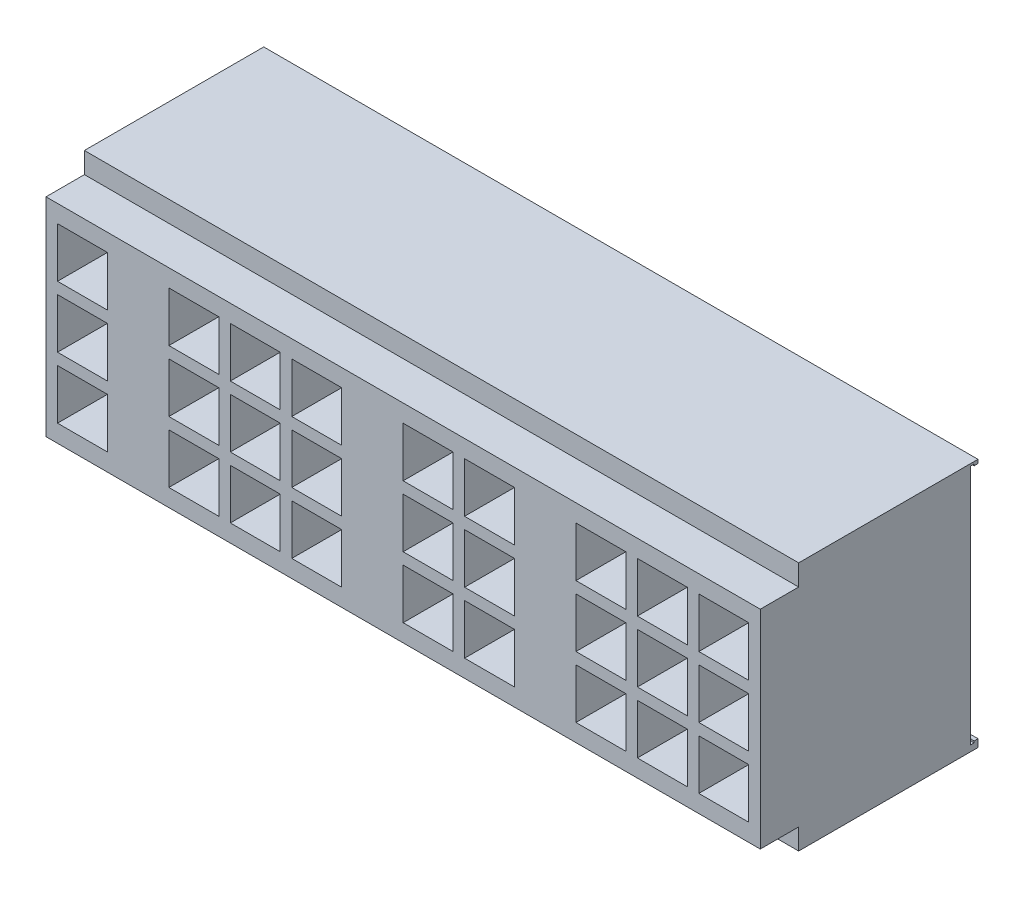
SolidWorks part; units mm, degrees
ref_plane "Plan de face" through (0, 0, 0) normal (0, 0, 1) x (1, 0, 0)
ref_plane "Plan de dessus" through (0, 0, 0) normal (0, 1, 0) x (1, 0, 0)
ref_plane "Plan de droite" through (0, 0, 0) normal (1, 0, 0) x (0, 0, -1)
sketch "Esquisse1" plane through (0, 0, 0) normal (0, 0, 1) x (1, 0, 0)
  line L1 (-93, -51) -> (93, -51)
  line L2 (-93, -51) -> (-93, 0)
  line L3 (-93, 0) -> (93, 0)
  line L4 (93, -51) -> (93, 0)
  line L13 (0, 49979.1071) -> (0, -49979.1071) construction
  point P0 (0, 0)
  point P16 (0, -51)
  point P17 (0, 0)
  point P27 (0, 0)
  dimension "D1" = 186
  dimension "D2" = 51
extrude "Boss.-Extru.1" add sketch "Esquisse1" along normal blind 20
sketch "Esquisse7" plane through (0, 0, 20) normal (0, 0, 1) x (1, 0, 0)
  line L0 (93, 0) -> (-93, 0) construction
  line L1 (-90, -3) -> (-77, -3)
  line L2 (-90, -3) -> (-90, -16)
  line L3 (-90, -16) -> (-77, -16)
  line L4 (-77, -3) -> (-77, -16)
  line L5 (-90, -3) -> (-77, -16) construction
  line L6 (-90, -16) -> (-77, -3) construction
  line L7 (-93, 0) -> (-93, -51) construction
  point P0 (-83.5, -9.5)
  dimension "D1" = 13
  dimension "D2" = 13
  dimension "D3" = 3
  dimension "D4" = 3
extrude "Enlèv. mat.-Extru.5" cut sketch "Esquisse7" against normal blind 91
pattern_linear "Répétition linéaire5" count 3 spacing 16 along (0, -1, 0) of "Enlèv. mat.-Extru.5"
sketch "Esquisse8" plane through (0, 0, 20) normal (0, 0, 1) x (1, 0, 0)
  line L0 (93, 0) -> (-93, 0) construction
  line L1 (-61, -3) -> (-48, -3)
  line L2 (-61, -3) -> (-61, -16)
  line L3 (-61, -16) -> (-48, -16)
  line L4 (-48, -3) -> (-48, -16)
  line L5 (-61, -3) -> (-48, -16) construction
  line L6 (-61, -16) -> (-48, -3) construction
  line L7 (-77, -16) -> (-77, -3) construction
  point P0 (-54.5, -9.5)
  dimension "D1" = 13
  dimension "D2" = 13
  dimension "D3" = 3
  dimension "D4" = 16
extrude "Enlèv. mat.-Extru.6" cut sketch "Esquisse8" against normal blind 103
pattern_linear "Répétition linéaire6" count 3 spacing 16 along (0, -1, 0) count 3 spacing 16 along (1, 0, 0) of "Enlèv. mat.-Extru.6"
sketch "Esquisse9" plane through (0, 0, 20) normal (0, 0, 1) x (1, 0, 0)
  line L0 (-16, -16) -> (-16, -3) construction
  line L1 (0, -3) -> (13, -3)
  line L2 (0, -3) -> (0, -16)
  line L3 (0, -16) -> (13, -16)
  line L4 (13, -3) -> (13, -16)
  line L5 (0, -3) -> (13, -16) construction
  line L6 (0, -16) -> (13, -3) construction
  line L7 (93, 0) -> (-93, 0) construction
  point P0 (6.5, -9.5)
  dimension "D1" = 13
  dimension "D2" = 13
  dimension "D3" = 16
  dimension "D4" = 3
extrude "Enlèv. mat.-Extru.7" cut sketch "Esquisse9" against normal blind 77
pattern_linear "Répétition linéaire7" count 3 spacing 16 along (0, -1, 0) count 2 spacing 16 along (1, 0, 0) of "Enlèv. mat.-Extru.7"
sketch "Esquisse10" plane through (0, 0, 20) normal (0, 0, 1) x (1, 0, 0)
  line L0 (29, -16) -> (29, -3) construction
  line L1 (45, -3) -> (58, -3)
  line L2 (45, -3) -> (45, -16)
  line L3 (45, -16) -> (58, -16)
  line L4 (58, -3) -> (58, -16)
  line L5 (45, -3) -> (58, -16) construction
  line L6 (45, -16) -> (58, -3) construction
  line L7 (93, 0) -> (-93, 0) construction
  point P0 (51.5, -9.5)
  dimension "D1" = 13
  dimension "D2" = 13
  dimension "D3" = 16
  dimension "D4" = 3
extrude "Enlèv. mat.-Extru.8" cut sketch "Esquisse10" against normal blind 78
pattern_linear "Répétition linéaire8" count 3 spacing 16 along (1, 0, 0) count 3 spacing 16 along (0, -1, 0) of "Enlèv. mat.-Extru.8"
sketch "Esquisse14" plane through (0, -51, 0) normal (0, -1, 0) x (1, 0, 0)
  line L0 (0, 0) -> (-15.3262, 0) construction
  line L1 (-12.6631, 0) -> (-2.6631, 0)
  line L2 (-12.6631, 0) -> (-12.6631, 5)
  line L3 (-12.6631, 5) -> (-2.6631, 5)
  line L4 (-2.6631, 0) -> (-2.6631, 5)
  line L5 (-12.6631, 0) -> (-2.6631, 5) construction
  line L6 (-12.6631, 5) -> (-2.6631, 0) construction
  line L7 (-93, 0) -> (93, 0) construction
  point P0 (-7.6631, 2.5)
  point P5 (-15.3262, 0)
  point P6 (0, 0)
  point P10 (0, 0)
  point P12 (-7.6631, 0)
  point P13 (-7.6631, 0)
  dimension "D1" = 10
  dimension "D2" = 5
extrude "Boss.-Extru.3" add sketch "Esquisse14" along normal blind 7
sketch "Esquisse25" plane through (0, 0, 0) normal (0, 1, 0) x (1, 0, 0)
  line L1 (-93, 0) -> (93, 0)
  line L2 (-93, 0) -> (-93, -20)
  line L3 (-93, -20) -> (93, -20)
  line L4 (93, 0) -> (93, -20)
extrude "Boss.-Extru.7" add sketch "Esquisse25" along normal blind 7
sketch "Esquisse18" plane through (0, -51, 0) normal (0, -1, 0) x (1, 0, 0)
  line L0 (-93, 0) -> (93, 0)
  line L2 (93, 0) -> (93, 20)
  line L3 (93, 20) -> (-93, 20)
  line L4 (-93, 20) -> (-93, 0)
extrude "Boss.-Extru.5" add sketch "Esquisse18" along normal blind 7
sketch "Esquisse16" plane through (-93, 0, 0) normal (-1, 0, 0) x (0, 0, 1)
  line L0 (20, -58) -> (0, -58) construction
  line L1 (20, 7) -> (20, -58) construction
  line L3 (20, -53) -> (16.7, -53)
  line L4 (16.7, -53) -> (16.7, 2)
  line L5 (16.7, 2) -> (20, 2)
  line L6 (20, 2) -> (20, -53)
  line L8 (0, 7) -> (20, 7) construction
  point P1 (18.35, -53)
  dimension "D1" = 5
  dimension "D4" = 5
  dimension "D5" = 3.3
extrude "Enlèv. mat.-Extru.11" cut sketch "Esquisse16" against normal blind 184
sketch "Esquisse15" plane through (0, 0, 0) normal (0, 0, -1) x (-1, 0, 0)
  circle A0 centre (8.4823, -42.4466) radius 1
  circle A1 centre (8.4823, -9.749) radius 1
  circle A2 centre (68.823, -42.4466) radius 1
  circle A3 centre (68.823, -9.749) radius 1
  circle A4 centre (-37.1355, -42.4466) radius 1
  circle A5 centre (-39.2159, -11.2606) radius 1
  dimension "D1" = 2
  dimension "D2" = 2
  dimension "D3" = 2
  dimension "D4" = 2
  dimension "D5" = 2
  dimension "D6" = 2
extrude "Enlèv. mat.-Extru.10" cut sketch "Esquisse15" against normal blind 7
sketch "Esquisse24" plane through (0, 0, 0) normal (0, 0, -1) x (-1, 0, 0)
  line L0 (77, -48) -> (90, -48) construction
  line L1 (88.5, -48) -> (78.5, -48)
  line L2 (88.5, -48) -> (88.5, -50)
  line L3 (88.5, -50) -> (78.5, -50)
  line L4 (78.5, -48) -> (78.5, -50)
  line L5 (48, -48) -> (61, -48) construction
  line L6 (59.5, -48) -> (49.5, -48)
  line L7 (59.5, -48) -> (59.5, -50)
  line L8 (59.5, -50) -> (49.5, -50)
  line L9 (49.5, -48) -> (49.5, -50)
  line L10 (32, -48) -> (45, -48) construction
  line L11 (43.5, -48) -> (33.5, -48)
  line L12 (43.5, -48) -> (43.5, -50)
  line L13 (43.5, -50) -> (33.5, -50)
  line L14 (33.5, -48) -> (33.5, -50)
  line L15 (16, -48) -> (29, -48) construction
  line L16 (27.5, -48) -> (17.5, -48)
  line L17 (27.5, -48) -> (27.5, -50)
  line L18 (27.5, -50) -> (17.5, -50)
  line L19 (17.5, -48) -> (17.5, -50)
  line L20 (-13, -48) -> (0, -48) construction
  line L21 (-1.5, -48) -> (-11.5, -48)
  line L22 (-1.5, -48) -> (-1.5, -50)
  line L23 (-1.5, -50) -> (-11.5, -50)
  line L24 (-11.5, -48) -> (-11.5, -50)
  line L25 (-29, -48) -> (-16, -48) construction
  line L26 (-17.5, -48) -> (-27.5, -48)
  line L27 (-17.5, -48) -> (-17.5, -50)
  line L28 (-17.5, -50) -> (-27.5, -50)
  line L29 (-27.5, -48) -> (-27.5, -50)
  line L30 (-58, -48) -> (-45, -48) construction
  line L31 (-46.5, -48) -> (-56.5, -48)
  line L32 (-46.5, -48) -> (-46.5, -50)
  line L33 (-46.5, -50) -> (-56.5, -50)
  line L34 (-56.5, -48) -> (-56.5, -50)
  line L35 (-74, -48) -> (-61, -48) construction
  line L36 (-62.5, -48) -> (-72.5, -48)
  line L37 (-62.5, -48) -> (-62.5, -50)
  line L38 (-62.5, -50) -> (-72.5, -50)
  line L39 (-72.5, -48) -> (-72.5, -50)
  line L40 (-90, -48) -> (-77, -48) construction
  line L41 (-78.5, -48) -> (-88.5, -48)
  line L42 (-78.5, -48) -> (-78.5, -50)
  line L43 (-78.5, -50) -> (-88.5, -50)
  line L44 (-88.5, -48) -> (-88.5, -50)
  line L45 (-77, -3) -> (-90, -3) construction
  line L46 (-78.5, -3) -> (-88.5, -3)
  line L47 (-78.5, -3) -> (-78.5, -1)
  line L48 (-78.5, -1) -> (-88.5, -1)
  line L49 (-88.5, -3) -> (-88.5, -1)
  line L50 (-61, -3) -> (-74, -3) construction
  line L51 (-62.5, -3) -> (-72.5, -3)
  line L52 (-62.5, -3) -> (-62.5, -1)
  line L53 (-62.5, -1) -> (-72.5, -1)
  line L54 (-72.5, -3) -> (-72.5, -1)
  line L55 (-45, -3) -> (-58, -3) construction
  line L56 (-46.5, -3) -> (-56.5, -3)
  line L57 (-46.5, -3) -> (-46.5, -1)
  line L58 (-46.5, -1) -> (-56.5, -1)
  line L59 (-56.5, -3) -> (-56.5, -1)
  line L60 (-16, -3) -> (-29, -3) construction
  line L61 (-17.5, -3) -> (-27.5, -3)
  line L62 (-17.5, -3) -> (-17.5, -1)
  line L63 (-17.5, -1) -> (-27.5, -1)
  line L64 (-27.5, -3) -> (-27.5, -1)
  line L65 (0, -3) -> (-13, -3) construction
  line L66 (-1.5, -3) -> (-11.5, -3)
  line L67 (-1.5, -3) -> (-1.5, -1)
  line L68 (-1.5, -1) -> (-11.5, -1)
  line L69 (-11.5, -3) -> (-11.5, -1)
  line L70 (29, -3) -> (16, -3) construction
  line L71 (17.5, -3) -> (27.5, -3)
  line L72 (17.5, -3) -> (17.5, -1)
  line L73 (17.5, -1) -> (27.5, -1)
  line L74 (27.5, -3) -> (27.5, -1)
  line L75 (45, -3) -> (32, -3) construction
  line L76 (33.5, -3) -> (43.5, -3)
  line L77 (33.5, -3) -> (33.5, -1)
  line L78 (33.5, -1) -> (43.5, -1)
  line L79 (43.5, -3) -> (43.5, -1)
  line L80 (61, -3) -> (48, -3) construction
  line L81 (49.5, -3) -> (59.5, -3)
  line L82 (49.5, -3) -> (49.5, -1)
  line L83 (49.5, -1) -> (59.5, -1)
  line L84 (59.5, -3) -> (59.5, -1)
  line L85 (90, -3) -> (77, -3) construction
  line L86 (78.5, -3) -> (88.5, -3)
  line L87 (78.5, -3) -> (78.5, -1)
  line L88 (78.5, -1) -> (88.5, -1)
  line L89 (88.5, -3) -> (88.5, -1)
  point P108 (83.5, -48)
  point P109 (54.5, -48)
  point P110 (38.5, -48)
  point P111 (22.5, -48)
  point P112 (-6.5, -48)
  point P113 (-22.5, -48)
  point P114 (-51.5, -48)
  point P115 (-67.5, -48)
  point P116 (-83.5, -48)
  point P117 (-83.5, -3)
  point P118 (-67.5, -3)
  point P119 (-51.5, -3)
  point P120 (-22.5, -3)
  point P121 (-6.5, -3)
  point P122 (22.5, -3)
  point P123 (38.5, -3)
  point P124 (54.5, -3)
  point P125 (83.5, -3)
  point P126 (83.5, -3)
  point P128 (54.5, -3)
  point P130 (38.5, -3)
  point P132 (22.5, -3)
  point P134 (-6.5, -3)
  point P136 (-22.5, -3)
  point P138 (-51.5, -3)
  point P140 (-67.5, -3)
  point P143 (-83.5, -3)
  point P145 (-83.5, -48)
  point P148 (-51.5, -48)
  point P150 (-22.5, -48)
  point P152 (-6.5, -48)
  point P154 (22.5, -48)
  point P156 (38.5, -48)
  point P159 (54.5, -48)
  point P161 (83.5, -48)
  dimension "D1" = 10
  dimension "D2" = 10
  dimension "D3" = 10
  dimension "D4" = 10
  dimension "D5" = 10
  dimension "D6" = 10
  dimension "D7" = 10
  dimension "D8" = 10
  dimension "D9" = 10
  dimension "D10" = 10
  dimension "D11" = 10
  dimension "D12" = 10
  dimension "D13" = 10
  dimension "D14" = 10
  dimension "D15" = 10
  dimension "D16" = 10
  dimension "D17" = 10
  dimension "D18" = 10
  dimension "D19" = 2
  dimension "D20" = 2
  dimension "D21" = 2
  dimension "D22" = 2
  dimension "D23" = 2
  dimension "D24" = 2
  dimension "D25" = 2
  dimension "D26" = 2
  dimension "D27" = 2
  dimension "D28" = 2
  dimension "D29" = 2
  dimension "D30" = 2
  dimension "D31" = 2
  dimension "D32" = 2
  dimension "D33" = 2
  dimension "D34" = 2
  dimension "D35" = 2
  dimension "D36" = 2
extrude "Enlèv. mat.-Extru.12" cut sketch "Esquisse24" against normal blind 1
sketch "Esquisse19" plane through (0, 0, 0) normal (0, 0, -1) x (-1, 0, 0)
  line L0 (-93, -58) -> (-93, 7) construction
  line L1 (93, -58) -> (-93, -58)
  line L2 (93, -58) -> (93, -56)
  line L3 (93, -56) -> (-93, -56)
  line L4 (-93, -58) -> (-93, -56)
  line L5 (93, 7) -> (93, -58) construction
  line L6 (-93, 7) -> (93, 7)
  line L7 (-93, 7) -> (-93, 5)
  line L8 (-93, 5) -> (93, 5)
  line L9 (93, 7) -> (93, 5)
  line L11 (-93, -56) -> (-91, -56)
  line L12 (-93, -56) -> (-93, 5)
  line L13 (-93, 5) -> (-91, 5)
  line L14 (-91, -56) -> (-91, 5)
  line L15 (93, 5) -> (91, 5)
  line L16 (93, 5) -> (93, -56)
  line L17 (93, -56) -> (91, -56)
  line L18 (91, 5) -> (91, -56)
  dimension "D1" = 2
  dimension "D2" = 2
  dimension "D3" = 2
  dimension "D4" = 2
extrude "Boss.-Extru.8" add sketch "Esquisse19" along normal blind 40 contours L4 L1 L2 L3 | L8 L18 L3 L16 | L9 L6 L7 L8 | L3 L14 L8 L12
sketch "Esquisse26" plane through (-93, 0, 0) normal (-1, 0, 0) x (0, 0, 1)
  line L0 (-40, -58) -> (-10, 7) construction
  line L1 (-40, 7) -> (20, 7) construction
  line L2 (-40, 7) -> (-10, -58) construction
  line L3 (20, -58) -> (-40, -58) construction
  circle A0 centre (-25, -25.5) radius 1.75
  dimension "D1" = 3.5
extrude "Enlèv. mat.-Extru.14" cut sketch "Esquisse26" against normal blind 30
sketch "Esquisse27" plane through (-93, 0, 0) normal (-1, 0, 0) x (0, 0, 1)
  line L1 (6.7, 2) -> (6.7, 7)
  line L2 (-40, 7) -> (20, 7) construction
  line L3 (6.7, 7) -> (20, 7)
  line L4 (20, 7) -> (20, -58)
  line L5 (20, -58) -> (6.7, -58)
  line L6 (20, -58) -> (-40, -58) construction
  line L7 (16.7, 1.55) -> (6.7, 1.55)
  line L8 (6.7, -53) -> (6.7, -58)
  line L9 (16.7, -53) -> (16.7, 2)
  line L10 (6.7, -53) -> (6.7, -52.55)
  line L11 (6.7, -52.55) -> (16.7, -52.55)
  line L12 (6.7, 1.55) -> (6.7, 2)
  point P16 (16.7, -52.55)
  point P17 (16.7, 1.55)
  dimension "D1" = 10
  dimension "D2" = 10
  dimension "D3" = 0.45
  dimension "D4" = 0.45
extrude "Enlèv. mat.-Extru.16" cut sketch "Esquisse27" against normal through all
sketch "Esquisse29" plane through (0, 0, -40) normal (0, 0, -1) x (-1, 0, 0)
  line L0 (-91, -56) -> (-93, -56) construction
  line L1 (-93, -58) -> (-93, 7) construction
sketch "Esquisse30" plane through (93, 0, 0) normal (1, 0, 0) x (0, 0, -1)
  line L1 (38, -56) -> (38, -56.45)
  line L2 (38, -56.45) -> (39, -56.45)
  line L3 (40, -58) -> (40, 7) construction
  line L4 (39, -56.45) -> (39, 6.45)
  line L5 (40, -56) -> (39, -56)
  line L6 (38, -56) -> (38, 6.45)
  line L7 (38, 6.45) -> (40, 6.45)
  line L8 (40, -56) -> (40, 6.0336)
  line L10 (40, 6.0336) -> (39, 6.0336)
  line M11 (40, -58) -> (40, 7)
  dimension "D1" = 0.45
extrude "Enlèv. mat.-Extru.19" cut sketch "Esquisse30" against normal blind 185.5 contours L7 L6 L1 L2 L4 | L10 L4 L5 M11
